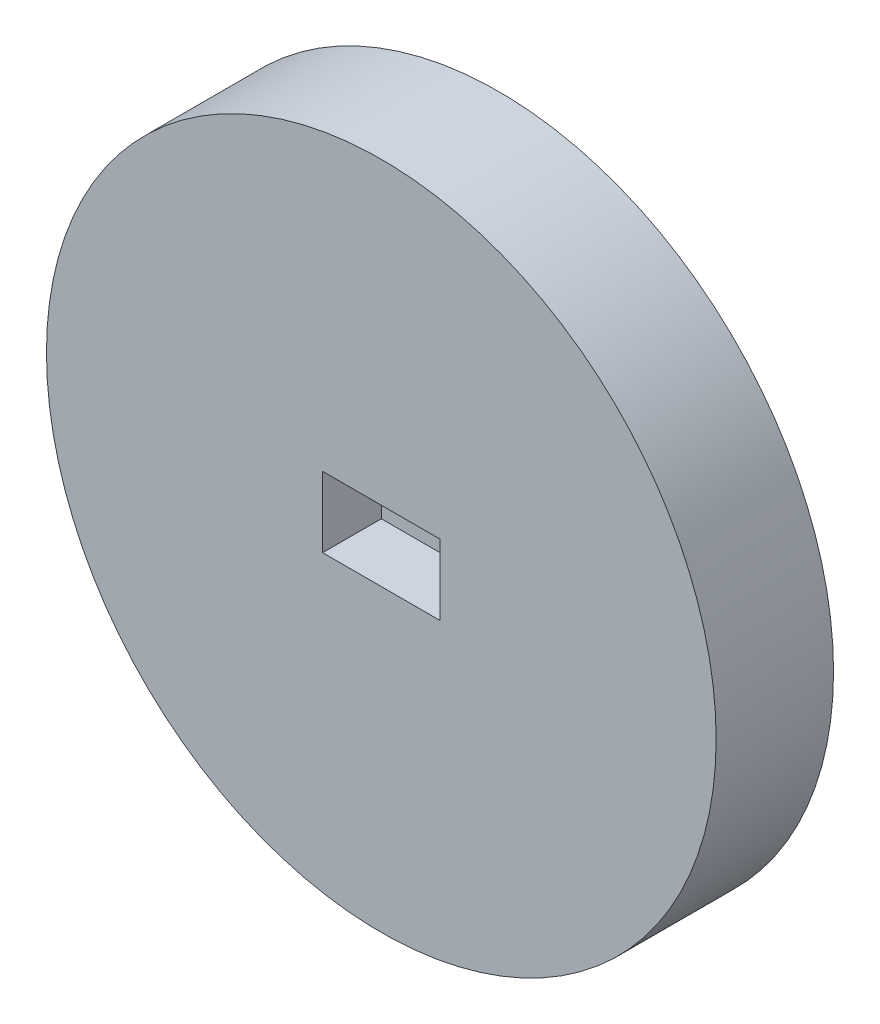
SolidWorks part; units mm, degrees
ref_plane "Piano frontale" through (0, 0, 0) normal (0, 0, 1) x (1, 0, 0)
ref_plane "Piano superiore" through (0, 0, 0) normal (0, 1, 0) x (1, 0, 0)
ref_plane "Piano destro" through (0, 0, 0) normal (1, 0, 0) x (0, 0, -1)
sketch "Schizzo1" plane through (0, 0, 0) normal (0, 0, 1) x (1, 0, 0)
  circle A0 centre (0, 0) radius 28.5252
extrude "Estrusione-Estrusione2" add sketch "Schizzo1" along normal mid plane 10
sketch "Schizzo4" plane through (0, 0, 5) normal (0, 0, 1) x (1, 0, 0)
  line L1 (-5, 3) -> (5, 3)
  line L2 (-5, 3) -> (-5, -3)
  line L3 (-5, -3) -> (5, -3)
  line L4 (5, 3) -> (5, -3)
  line L5 (-5, 3) -> (5, -3) construction
  line L6 (-5, -3) -> (5, 3) construction
  point P0 (0, 0)
  dimension "D1" = 6
  dimension "D2" = 10
extrude "Taglio-Estrusione1" cut sketch "Schizzo4" against normal mid plane 10
